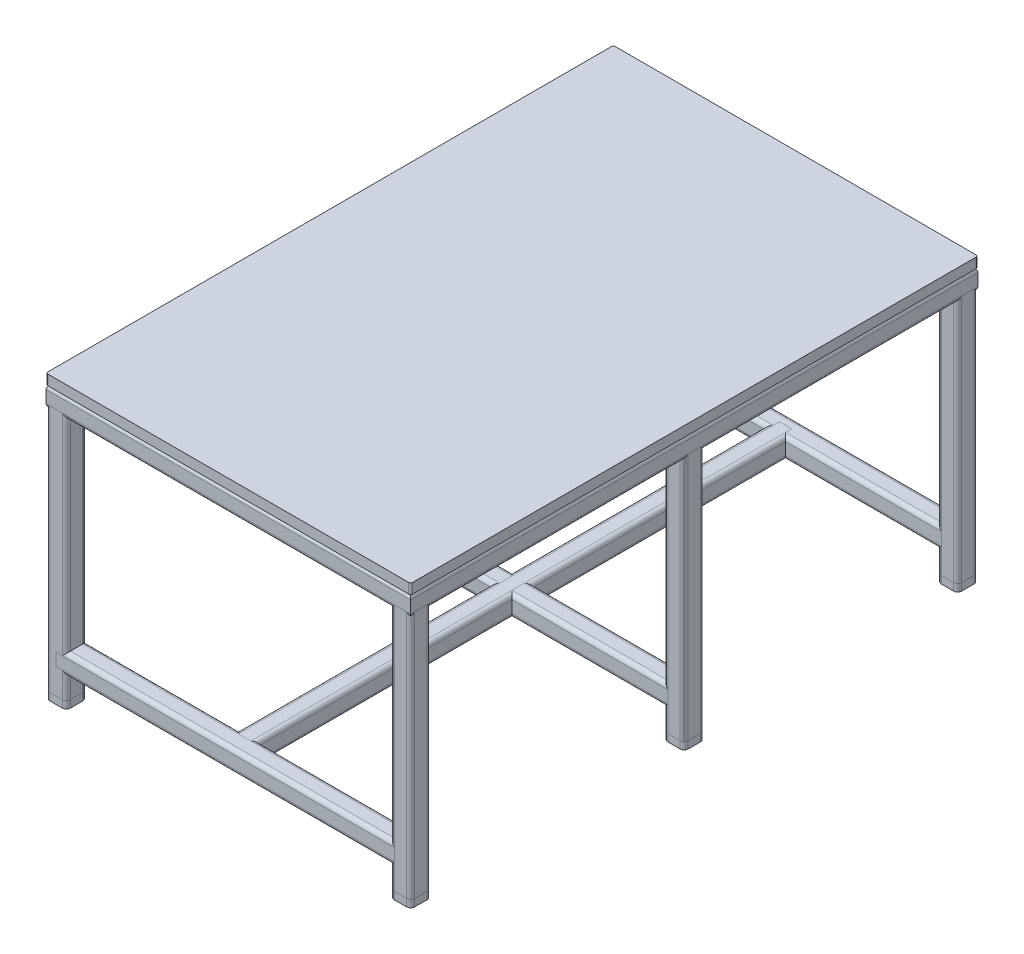
SolidWorks part; units mm, degrees
ref_plane "Front Plane" through (0, 0, 0) normal (0, 0, 1) x (1, 0, 0)
ref_plane "Top Plane" through (0, 0, 0) normal (0, 1, 0) x (1, 0, 0)
ref_plane "Right Plane" through (0, 0, 0) normal (1, 0, 0) x (0, 0, -1)
sketch "Sketch1" plane through (0, 0, 0) normal (0, 0, 1) x (1, 0, 0)
  line L0 (-169.1331, 187.1272) -> (-169.1331, -62.8728)
  line L1 (169.1331, 187.1272) -> (169.1331, -62.8728)
  line L2 (0, 187.1272) -> (0, -125.0187) construction
  line L3 (-169.1331, 187.1272) -> (169.1331, 187.1272)
  line L4 (-169.1331, -31.487) -> (169.1331, -31.487)
  dimension "D1" = 250
sketch3d "3DSketch1"
  line L0 (-169.1331, 187.1272, 0) -> (-169.1331, 187.1272, -537.3778)
  line L1 (-169.1331, 187.1272, -537.3778) -> (169.1331, 187.1272, -537.3778)
  line L2 (169.1331, 187.1272, -537.3778) -> (169.1331, 187.1272, 0)
  line L3 (-169.1331, 187.1272, 0) -> (169.1331, 187.1272, 0) construction
  line L4 (169.1331, 187.1272, -537.3778) -> (169.1331, -62.8728, -537.3778)
  line L5 (-169.1331, 187.1272, -537.3778) -> (-169.1331, -62.8728, -537.3778)
  line L6 (169.1331, 187.1272, 0) -> (169.1331, -62.8728, 0) construction
ref_plane "Plane1" through (0, 0, -537.3778) normal (0, 0, -1) x (-1, 0, 0)
sketch "Sketch2" plane through (0, 0, -537.3778) normal (0, 0, -1) x (-1, 0, 0)
  line L0 (169.1331, -31.487) -> (-169.1331, -31.487) construction
  line L1 (169.1331, -31.487) -> (-169.1331, -31.487)
sketch3d "3DSketch2"
  line L0 (0, -31.487, 0) -> (0, -31.487, -537.3778)
  line L1 (-169.1331, -31.487, 0) -> (169.1331, -31.487, 0) construction
  line L2 (-169.1331, -31.487, -537.3778) -> (169.1331, -31.487, -537.3778) construction
  line L3 (169.1331, 187.1272, -268.6889) -> (169.1331, -62.8728, -268.6889)
  line L4 (169.1331, 187.1272, -537.3778) -> (169.1331, 187.1272, 0) construction
  line L5 (-169.1331, 187.1272, -268.6889) -> (-169.1331, -62.8728, -268.6889)
  line L6 (-169.1331, 187.1272, 0) -> (-169.1331, 187.1272, -537.3778) construction
  line L7 (-169.1331, -31.487, 0) -> (-169.1331, -31.487, -537.3778)
  line L8 (169.1331, -31.487, -537.3778) -> (169.1331, -31.487, 0)
  line L9 (-169.1331, -31.487, -268.6889) -> (169.1331, -31.487, -268.6889)
other "Square tube 20 X 20 X 2(37)"
ref_plane "Plane2" through (-169.1331, 187.1272, 0) normal (1, 0, 0) x (0, 1, 0)
sketch "Sketch116" plane through (-169.1331, 187.1272, 0) normal (1, 0, 0) x (0, 1, 0)
  line L0 (-6, -8) -> (6, -8)
  line L1 (-8, -6) -> (-8, 6)
  line L2 (6, 8) -> (-6, 8)
  line L3 (8, 6) -> (8, -6)
  line L4 (-6, -10) -> (6, -10)
  line L5 (-10, -6) -> (-10, 6)
  line L6 (6, 10) -> (-6, 10)
  line L7 (10, 6) -> (10, -6)
  arc A0 (10, 6) -> (6, 10) centre (6, 6) ccw
  arc A1 (6, -10) -> (10, -6) centre (6, -6) ccw
  arc A2 (-10, -6) -> (-6, -10) centre (-6, -6) ccw
  arc A3 (-6, 10) -> (-10, 6) centre (-6, 6) ccw
  arc A4 (-6, 8) -> (-8, 6) centre (-6, 6) ccw
  arc A5 (8, 6) -> (6, 8) centre (6, 6) ccw
  arc A6 (6, -8) -> (8, -6) centre (6, -6) ccw
  arc A7 (-8, -6) -> (-6, -8) centre (-6, -6) ccw
  point P0 (-10, 0)
  point P1 (10, 0)
  point P2 (0, 10)
  point P3 (0, -10)
  point P4 (0, 0)
  point P5 (-10, -10)
  point P6 (10, -10)
  point P7 (10, 10)
  point P8 (-10, 10)
  point P33 (0, 0)
  dimension "D1" = 4
  dimension "Thickness" = 2
  dimension "V_leg" = 20
sketch "Sketch14" plane through (0, 197.1272, 0) normal (0, 1, 0) x (1, 0, 0)
  line L0 (0, 0) -> (0, 537.3778) construction
  line L1 (-179.1331, -10) -> (179.1331, -10)
  line L2 (-179.1331, -10) -> (-179.1331, 547.3778)
  line L3 (-179.1331, 547.3778) -> (179.1331, 547.3778)
  line L4 (179.1331, -10) -> (179.1331, 547.3778)
  line L5 (-179.1331, -10) -> (179.1331, 547.3778) construction
  line L6 (-179.1331, 547.3778) -> (179.1331, -10) construction
  line L7 (-179.1331, 268.6889) -> (179.1331, 268.6889) construction
  line L8 (179.1331, -10) -> (-179.1331, -10) construction
  line L9 (-179.1331, -10) -> (-179.1331, 547.3778) construction
  point P0 (0, 268.6889)
extrude "Boss-Extrude1" add sketch "Sketch14" along normal blind 10 separate body
other "Square tube 20 X 20 X 2(6)"
ref_plane "Plane6" through (-169.1331, 187.1272, -268.6889) normal (0, -1, 0) x (1, 0, 0)
sketch "Sketch18" plane through (-169.1331, 187.1272, -268.6889) normal (0, -1, 0) x (1, 0, 0)
  line L0 (-6, -8) -> (6, -8)
  line L1 (-8, -6) -> (-8, 6)
  line L2 (6, 8) -> (-6, 8)
  line L3 (8, 6) -> (8, -6)
  line L4 (-6, -10) -> (6, -10)
  line L5 (-10, -6) -> (-10, 6)
  line L6 (6, 10) -> (-6, 10)
  line L7 (10, 6) -> (10, -6)
  arc A0 (10, 6) -> (6, 10) centre (6, 6) ccw
  arc A1 (6, -10) -> (10, -6) centre (6, -6) ccw
  arc A2 (-10, -6) -> (-6, -10) centre (-6, -6) ccw
  arc A3 (-6, 10) -> (-10, 6) centre (-6, 6) ccw
  arc A4 (-6, 8) -> (-8, 6) centre (-6, 6) ccw
  arc A5 (8, 6) -> (6, 8) centre (6, 6) ccw
  arc A6 (6, -8) -> (8, -6) centre (6, -6) ccw
  arc A7 (-8, -6) -> (-6, -8) centre (-6, -6) ccw
  point P0 (-10, 0)
  point P1 (10, 0)
  point P2 (0, 10)
  point P3 (0, -10)
  point P4 (0, 0)
  point P5 (-10, -10)
  point P6 (10, -10)
  point P7 (10, 10)
  point P8 (-10, 10)
  point P33 (0, 0)
  dimension "D1" = 4
  dimension "Thickness" = 2
  dimension "V_leg" = 20
ref_plane "Plane7" through (0, 0, -268.6889) normal (0, 0, 1) x (1, 0, 0)
fillet "Fillet4" radius 2 4 edges at (179.1331, 202.1272, -547.3778) (-179.1331, 202.1272, -547.3778) (-179.1331, 202.1272, 10) (179.1331, 202.1272, 10)
other "Square tube 20 X 20 X 2(11)"
ref_plane "Plane9" through (-169.1331, -31.487, -268.6889) normal (1, 0, 0) x (0, 0, -1)
sketch "Sketch110" plane through (-169.1331, -31.487, -268.6889) normal (1, 0, 0) x (0, 0, -1)
  line L0 (-6, -8) -> (6, -8)
  line L1 (-8, -6) -> (-8, 6)
  line L2 (6, 8) -> (-6, 8)
  line L3 (8, 6) -> (8, -6)
  line L4 (-6, -10) -> (6, -10)
  line L5 (-10, -6) -> (-10, 6)
  line L6 (6, 10) -> (-6, 10)
  line L7 (10, 6) -> (10, -6)
  arc A0 (10, 6) -> (6, 10) centre (6, 6) ccw
  arc A1 (6, -10) -> (10, -6) centre (6, -6) ccw
  arc A2 (-10, -6) -> (-6, -10) centre (-6, -6) ccw
  arc A3 (-6, 10) -> (-10, 6) centre (-6, 6) ccw
  arc A4 (-6, 8) -> (-8, 6) centre (-6, 6) ccw
  arc A5 (8, 6) -> (6, 8) centre (6, 6) ccw
  arc A6 (6, -8) -> (8, -6) centre (6, -6) ccw
  arc A7 (-8, -6) -> (-6, -8) centre (-6, -6) ccw
  point P0 (-10, 0)
  point P1 (10, 0)
  point P2 (0, 10)
  point P3 (0, -10)
  point P4 (0, 0)
  point P5 (-10, -10)
  point P6 (10, -10)
  point P7 (10, 10)
  point P8 (-10, 10)
  point P33 (0, 0)
  dimension "D1" = 4
  dimension "Thickness" = 2
  dimension "V_leg" = 20
ref_plane "Plane10" through (0, -70, 0) normal (0, 1, 0) x (1, 0, 0)
other "Square tube 20 X 20 X 2(44)"
ref_plane "Plane12" through (-169.1331, 187.1272, 0) normal (0, -1, 0) x (1, 0, 0)
sketch "Sketch118" plane through (-169.1331, 187.1272, 0) normal (0, -1, 0) x (1, 0, 0)
  line L0 (-6, -8) -> (6, -8)
  line L1 (-8, -6) -> (-8, 6)
  line L2 (6, 8) -> (-6, 8)
  line L3 (8, 6) -> (8, -6)
  line L4 (-6, -10) -> (6, -10)
  line L5 (-10, -6) -> (-10, 6)
  line L6 (6, 10) -> (-6, 10)
  line L7 (10, 6) -> (10, -6)
  arc A0 (10, 6) -> (6, 10) centre (6, 6) ccw
  arc A1 (6, -10) -> (10, -6) centre (6, -6) ccw
  arc A2 (-10, -6) -> (-6, -10) centre (-6, -6) ccw
  arc A3 (-6, 10) -> (-10, 6) centre (-6, 6) ccw
  arc A4 (-6, 8) -> (-8, 6) centre (-6, 6) ccw
  arc A5 (8, 6) -> (6, 8) centre (6, 6) ccw
  arc A6 (6, -8) -> (8, -6) centre (6, -6) ccw
  arc A7 (-8, -6) -> (-6, -8) centre (-6, -6) ccw
  point P0 (-10, 0)
  point P1 (10, 0)
  point P2 (0, 10)
  point P3 (0, -10)
  point P4 (0, 0)
  point P5 (-10, -10)
  point P6 (10, -10)
  point P7 (10, 10)
  point P8 (-10, 10)
  point P33 (0, 0)
  dimension "D1" = 4
  dimension "Thickness" = 2
  dimension "V_leg" = 20
sketch "Sketch119" plane through (0, -70, 0) normal (0, 1, 0) x (1, 0, 0)
  line L0 (-163.1331, 527.3778) -> (-175.1331, 527.3778) construction
  line L1 (-179.1331, 531.3778) -> (-179.1331, 543.3778) construction
  line L2 (-175.1331, 547.3778) -> (-163.1331, 547.3778) construction
  line L3 (-159.1331, 543.3778) -> (-159.1331, 531.3778) construction
  line L4 (175.1331, 527.3778) -> (163.1331, 527.3778) construction
  line L5 (159.1331, 531.3778) -> (159.1331, 543.3778) construction
  line L6 (163.1331, 547.3778) -> (175.1331, 547.3778) construction
  line L7 (179.1331, 543.3778) -> (179.1331, 531.3778) construction
  line L8 (175.1331, 258.6889) -> (163.1331, 258.6889) construction
  line L9 (159.1331, 262.6889) -> (159.1331, 274.6889) construction
  line L10 (163.1331, 278.6889) -> (175.1331, 278.6889) construction
  line L11 (179.1331, 274.6889) -> (179.1331, 262.6889) construction
  line L12 (175.1331, -10) -> (163.1331, -10) construction
  line L13 (159.1331, -6) -> (159.1331, 6) construction
  line L14 (163.1331, 10) -> (175.1331, 10) construction
  line L15 (179.1331, 6) -> (179.1331, -6) construction
  line L16 (-163.1331, -10) -> (-175.1331, -10) construction
  line L17 (-179.1331, -6) -> (-179.1331, 6) construction
  line L18 (-175.1331, 10) -> (-163.1331, 10) construction
  line L19 (-159.1331, 6) -> (-159.1331, -6) construction
  line L20 (-163.1331, 258.6889) -> (-175.1331, 258.6889) construction
  line L21 (-179.1331, 262.6889) -> (-179.1331, 274.6889) construction
  line L22 (-175.1331, 278.6889) -> (-163.1331, 278.6889) construction
  line L23 (-159.1331, 274.6889) -> (-159.1331, 262.6889) construction
  line L24 (-163.1331, 527.3778) -> (-175.1331, 527.3778)
  line L25 (-179.1331, 531.3778) -> (-179.1331, 543.3778)
  line L26 (-175.1331, 547.3778) -> (-163.1331, 547.3778)
  line L27 (-159.1331, 543.3778) -> (-159.1331, 531.3778)
  line L28 (175.1331, 527.3778) -> (163.1331, 527.3778)
  line L29 (159.1331, 531.3778) -> (159.1331, 543.3778)
  line L30 (163.1331, 547.3778) -> (175.1331, 547.3778)
  line L31 (179.1331, 543.3778) -> (179.1331, 531.3778)
  line L32 (175.1331, 258.6889) -> (163.1331, 258.6889)
  line L33 (159.1331, 262.6889) -> (159.1331, 274.6889)
  line L34 (163.1331, 278.6889) -> (175.1331, 278.6889)
  line L35 (179.1331, 274.6889) -> (179.1331, 262.6889)
  line L36 (175.1331, -10) -> (163.1331, -10)
  line L37 (159.1331, -6) -> (159.1331, 6)
  line L38 (163.1331, 10) -> (175.1331, 10)
  line L39 (179.1331, 6) -> (179.1331, -6)
  line L40 (-163.1331, -10) -> (-175.1331, -10)
  line L41 (-179.1331, -6) -> (-179.1331, 6)
  line L42 (-175.1331, 10) -> (-163.1331, 10)
  line L43 (-159.1331, 6) -> (-159.1331, -6)
  line L44 (-163.1331, 258.6889) -> (-175.1331, 258.6889)
  line L45 (-179.1331, 262.6889) -> (-179.1331, 274.6889)
  line L46 (-175.1331, 278.6889) -> (-163.1331, 278.6889)
  line L47 (-159.1331, 274.6889) -> (-159.1331, 262.6889)
  arc A0 (-163.1331, 527.3778) -> (-159.1331, 531.3778) centre (-163.1331, 531.3778) ccw construction
  arc A1 (-179.1331, 531.3778) -> (-175.1331, 527.3778) centre (-175.1331, 531.3778) ccw construction
  arc A2 (-175.1331, 547.3778) -> (-179.1331, 543.3778) centre (-175.1331, 543.3778) ccw construction
  arc A3 (-159.1331, 543.3778) -> (-163.1331, 547.3778) centre (-163.1331, 543.3778) ccw construction
  arc A4 (175.1331, 527.3778) -> (179.1331, 531.3778) centre (175.1331, 531.3778) ccw construction
  arc A5 (159.1331, 531.3778) -> (163.1331, 527.3778) centre (163.1331, 531.3778) ccw construction
  arc A6 (163.1331, 547.3778) -> (159.1331, 543.3778) centre (163.1331, 543.3778) ccw construction
  arc A7 (179.1331, 543.3778) -> (175.1331, 547.3778) centre (175.1331, 543.3778) ccw construction
  arc A8 (175.1331, 258.6889) -> (179.1331, 262.6889) centre (175.1331, 262.6889) ccw construction
  arc A9 (159.1331, 262.6889) -> (163.1331, 258.6889) centre (163.1331, 262.6889) ccw construction
  arc A10 (163.1331, 278.6889) -> (159.1331, 274.6889) centre (163.1331, 274.6889) ccw construction
  arc A11 (179.1331, 274.6889) -> (175.1331, 278.6889) centre (175.1331, 274.6889) ccw construction
  arc A12 (175.1331, -10) -> (179.1331, -6) centre (175.1331, -6) ccw construction
  arc A13 (159.1331, -6) -> (163.1331, -10) centre (163.1331, -6) ccw construction
  arc A14 (163.1331, 10) -> (159.1331, 6) centre (163.1331, 6) ccw construction
  arc A15 (179.1331, 6) -> (175.1331, 10) centre (175.1331, 6) ccw construction
  arc A16 (-163.1331, -10) -> (-159.1331, -6) centre (-163.1331, -6) ccw construction
  arc A17 (-179.1331, -6) -> (-175.1331, -10) centre (-175.1331, -6) ccw construction
  arc A18 (-175.1331, 10) -> (-179.1331, 6) centre (-175.1331, 6) ccw construction
  arc A19 (-159.1331, 6) -> (-163.1331, 10) centre (-163.1331, 6) ccw construction
  arc A20 (-163.1331, 258.6889) -> (-159.1331, 262.6889) centre (-163.1331, 262.6889) ccw construction
  arc A21 (-179.1331, 262.6889) -> (-175.1331, 258.6889) centre (-175.1331, 262.6889) ccw construction
  arc A22 (-175.1331, 278.6889) -> (-179.1331, 274.6889) centre (-175.1331, 274.6889) ccw construction
  arc A23 (-159.1331, 274.6889) -> (-163.1331, 278.6889) centre (-163.1331, 274.6889) ccw construction
  arc A24 (-163.1331, 527.3778) -> (-159.1331, 531.3778) centre (-163.1331, 531.3778) ccw
  arc A25 (-179.1331, 531.3778) -> (-175.1331, 527.3778) centre (-175.1331, 531.3778) ccw
  arc A26 (-175.1331, 547.3778) -> (-179.1331, 543.3778) centre (-175.1331, 543.3778) ccw
  arc A27 (-159.1331, 543.3778) -> (-163.1331, 547.3778) centre (-163.1331, 543.3778) ccw
  arc A28 (175.1331, 527.3778) -> (179.1331, 531.3778) centre (175.1331, 531.3778) ccw
  arc A29 (159.1331, 531.3778) -> (163.1331, 527.3778) centre (163.1331, 531.3778) ccw
  arc A30 (163.1331, 547.3778) -> (159.1331, 543.3778) centre (163.1331, 543.3778) ccw
  arc A31 (179.1331, 543.3778) -> (175.1331, 547.3778) centre (175.1331, 543.3778) ccw
  arc A32 (175.1331, 258.6889) -> (179.1331, 262.6889) centre (175.1331, 262.6889) ccw
  arc A33 (159.1331, 262.6889) -> (163.1331, 258.6889) centre (163.1331, 262.6889) ccw
  arc A34 (163.1331, 278.6889) -> (159.1331, 274.6889) centre (163.1331, 274.6889) ccw
  arc A35 (179.1331, 274.6889) -> (175.1331, 278.6889) centre (175.1331, 274.6889) ccw
  arc A36 (175.1331, -10) -> (179.1331, -6) centre (175.1331, -6) ccw
  arc A37 (159.1331, -6) -> (163.1331, -10) centre (163.1331, -6) ccw
  arc A38 (163.1331, 10) -> (159.1331, 6) centre (163.1331, 6) ccw
  arc A39 (179.1331, 6) -> (175.1331, 10) centre (175.1331, 6) ccw
  arc A40 (-163.1331, -10) -> (-159.1331, -6) centre (-163.1331, -6) ccw
  arc A41 (-179.1331, -6) -> (-175.1331, -10) centre (-175.1331, -6) ccw
  arc A42 (-175.1331, 10) -> (-179.1331, 6) centre (-175.1331, 6) ccw
  arc A43 (-159.1331, 6) -> (-163.1331, 10) centre (-163.1331, 6) ccw
  arc A44 (-163.1331, 258.6889) -> (-159.1331, 262.6889) centre (-163.1331, 262.6889) ccw
  arc A45 (-179.1331, 262.6889) -> (-175.1331, 258.6889) centre (-175.1331, 262.6889) ccw
  arc A46 (-175.1331, 278.6889) -> (-179.1331, 274.6889) centre (-175.1331, 274.6889) ccw
  arc A47 (-159.1331, 274.6889) -> (-163.1331, 278.6889) centre (-163.1331, 274.6889) ccw
extrude "Boss-Extrude2" add sketch "Sketch119" along normal up to surface (7.1272 mm away) separate body up to face at (169.1331, -62.8728, -537.3778)
other "Square tube 20 X 20 X 2(46)"
ref_plane "Plane13" through (-169.1331, -31.487, 0) normal (1, 0, 0) x (0, 1, 0)
sketch "Sketch121" plane through (-169.1331, -31.487, 0) normal (1, 0, 0) x (0, 1, 0)
  line L0 (-6, -8) -> (6, -8)
  line L1 (-8, -6) -> (-8, 6)
  line L2 (6, 8) -> (-6, 8)
  line L3 (8, 6) -> (8, -6)
  line L4 (-6, -10) -> (6, -10)
  line L5 (-10, -6) -> (-10, 6)
  line L6 (6, 10) -> (-6, 10)
  line L7 (10, 6) -> (10, -6)
  arc A0 (10, 6) -> (6, 10) centre (6, 6) ccw
  arc A1 (6, -10) -> (10, -6) centre (6, -6) ccw
  arc A2 (-10, -6) -> (-6, -10) centre (-6, -6) ccw
  arc A3 (-6, 10) -> (-10, 6) centre (-6, 6) ccw
  arc A4 (-6, 8) -> (-8, 6) centre (-6, 6) ccw
  arc A5 (8, 6) -> (6, 8) centre (6, 6) ccw
  arc A6 (6, -8) -> (8, -6) centre (6, -6) ccw
  arc A7 (-8, -6) -> (-6, -8) centre (-6, -6) ccw
  point P0 (-10, 0)
  point P1 (10, 0)
  point P2 (0, 10)
  point P3 (0, -10)
  point P4 (0, 0)
  point P5 (-10, -10)
  point P6 (10, -10)
  point P7 (10, 10)
  point P8 (-10, 10)
  point P33 (0, 0)
  dimension "D1" = 4
  dimension "Thickness" = 2
  dimension "V_leg" = 20
other "Square tube 20 X 20 X 2(47)"
ref_plane "Plane14" through (0, -31.487, 0) normal (0, 0, -1) x (1, 0, 0)
sketch "Sketch122" plane through (0, -31.487, 0) normal (0, 0, -1) x (1, 0, 0)
  line L0 (-6, -8) -> (6, -8)
  line L1 (-8, -6) -> (-8, 6)
  line L2 (6, 8) -> (-6, 8)
  line L3 (8, 6) -> (8, -6)
  line L4 (-6, -10) -> (6, -10)
  line L5 (-10, -6) -> (-10, 6)
  line L6 (6, 10) -> (-6, 10)
  line L7 (10, 6) -> (10, -6)
  arc A0 (10, 6) -> (6, 10) centre (6, 6) ccw
  arc A1 (6, -10) -> (10, -6) centre (6, -6) ccw
  arc A2 (-10, -6) -> (-6, -10) centre (-6, -6) ccw
  arc A3 (-6, 10) -> (-10, 6) centre (-6, 6) ccw
  arc A4 (-6, 8) -> (-8, 6) centre (-6, 6) ccw
  arc A5 (8, 6) -> (6, 8) centre (6, 6) ccw
  arc A6 (6, -8) -> (8, -6) centre (6, -6) ccw
  arc A7 (-8, -6) -> (-6, -8) centre (-6, -6) ccw
  point P0 (-10, 0)
  point P1 (10, 0)
  point P2 (0, 10)
  point P3 (0, -10)
  point P4 (0, 0)
  point P5 (-10, -10)
  point P6 (10, -10)
  point P7 (10, 10)
  point P8 (-10, 10)
  point P33 (0, 0)
  dimension "D1" = 4
  dimension "Thickness" = 2
  dimension "V_leg" = 20
